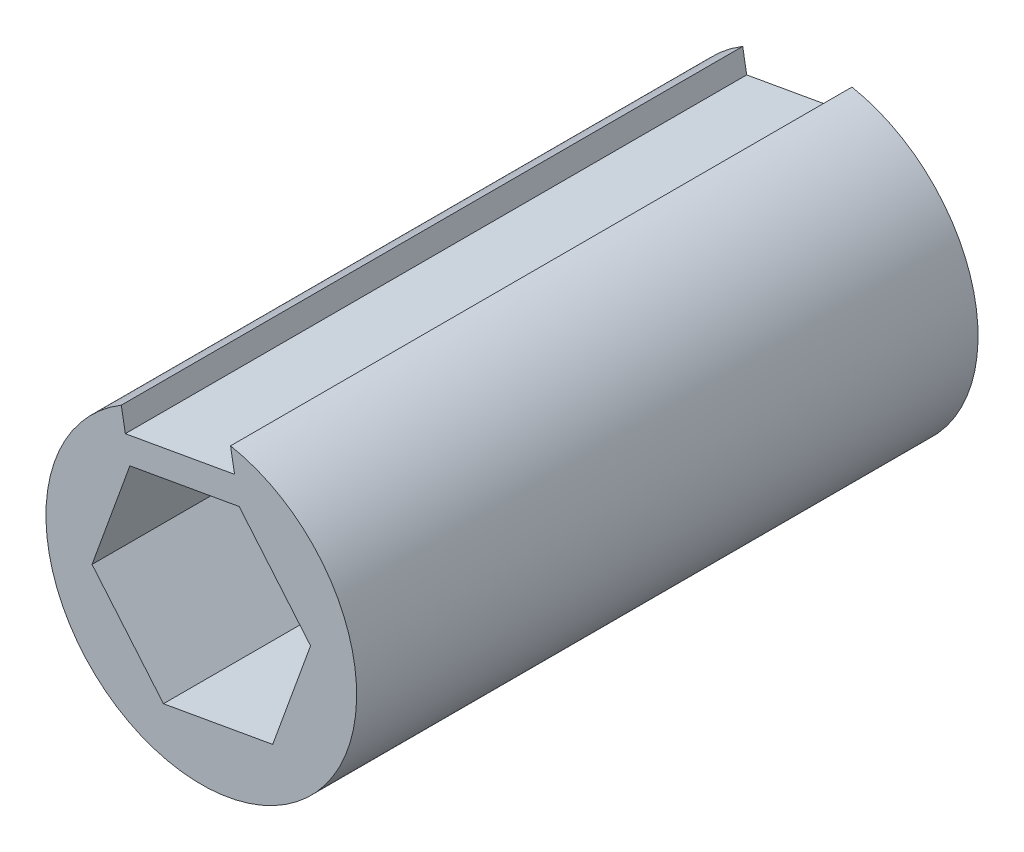
SolidWorks part; units mm, degrees
ref_plane "Płaszczyzna przednia" through (0, 0, 0) normal (0, 0, 1) x (1, 0, 0)
ref_plane "Płaszczyzna górna" through (0, 0, 0) normal (0, 1, 0) x (1, 0, 0)
ref_plane "Płaszczyzna prawa" through (0, 0, 0) normal (1, 0, 0) x (0, 0, -1)
sketch "Szkic1" plane through (0, 0, 0) normal (0, 0, 1) x (1, 0, 0)
  line L13 (4.923, 0.8741) -> (1.7045, 4.7005)
  line L14 (1.7045, 4.7005) -> (-3.2185, 3.8264)
  line L15 (-3.2185, 3.8264) -> (-4.923, -0.8741)
  line L16 (-4.923, -0.8741) -> (-1.7045, -4.7005)
  line L17 (-1.7045, -4.7005) -> (3.2185, -3.8264)
  line L18 (3.2185, -3.8264) -> (4.923, 0.8741)
  circle A0 centre (0, 0) radius 7
  circle A12 centre (0, 0) radius 4.3301 construction
  circle A13 centre (0, 0) radius 5 construction
  dimension "D7" = 10
  dimension "D1" = 14
extrude "Dodanie-wyciągnięcie1" add sketch "Szkic1" along normal blind 28
sketch "Szkic2" plane through (0, 0, 28) normal (0, 0, 1) x (1, 0, 0)
  line L0 (1.7045, 4.7005) -> (-3.2185, 3.8264) construction
  line L1 (-3.423, 4.9782) -> (1.4999, 5.8524)
  line L2 (-3.423, 4.9782) -> (-3.6853, 6.4551)
  line L3 (-3.6853, 6.4551) -> (1.2377, 7.3293)
  line L4 (1.4999, 5.8524) -> (1.2377, 7.3293)
  line L5 (-1.2238, 6.8922) -> (0, 0) construction
  circle A0 centre (0, 0) radius 7 construction
  point P4 (0, 0)
  point P7 (-2.197, 8.577)
  dimension "D1" = 1.5
  dimension "D2" = 5
extrude "Wytnij-wyciągnięcie1" cut sketch "Szkic2" against normal through all
